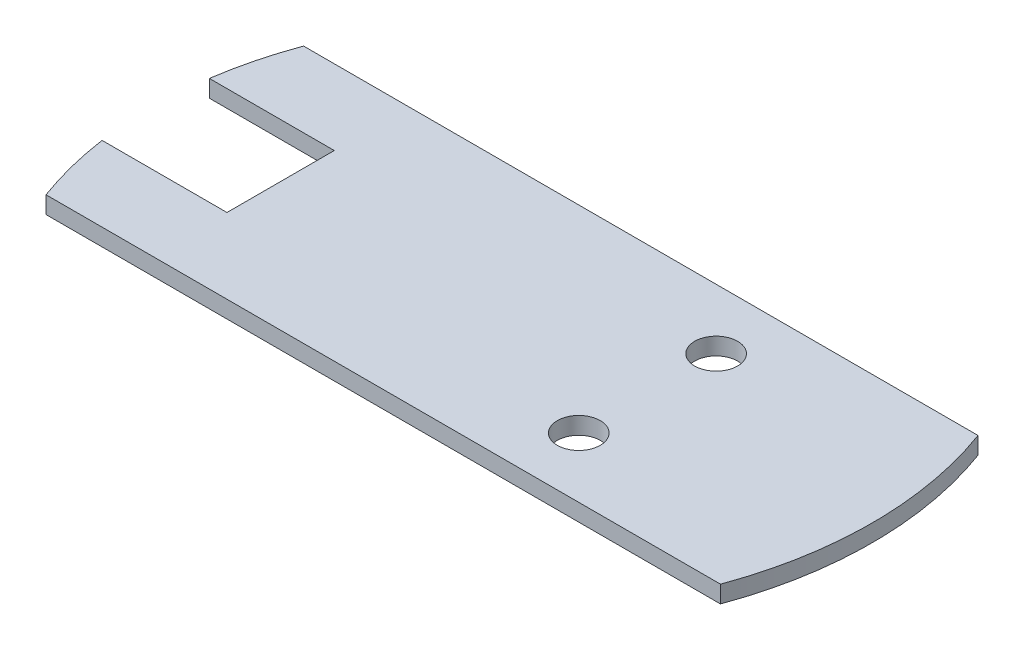
SolidWorks part; units mm, degrees
ref_plane "Front Plane" through (0, 0, 0) normal (0, 0, 1) x (1, 0, 0)
ref_plane "Top Plane" through (0, 0, 0) normal (0, 1, 0) x (1, 0, 0)
ref_plane "Right Plane" through (0, 0, 0) normal (1, 0, 0) x (0, 0, -1)
sketch "Sketch1" plane through (0, 0, 0) normal (0, 1, 0) x (1, 0, 0)
  line L0 (-145.5499, 0) -> (145.5499, 0) construction
  line L1 (-39.2787, 15) -> (39.2787, 15)
  line L2 (-39.2787, 15) -> (-39.2787, -15) construction
  line L3 (-39.2787, -15) -> (39.2787, -15)
  line L4 (39.2787, 15) -> (39.2787, -15) construction
  line L5 (-39.2787, 15) -> (39.2787, -15) construction
  line L6 (-39.2787, -15) -> (39.2787, 15) construction
  line L7 (0, 15) -> (0, -15) construction
  line L8 (-41.95, 85.2716) -> (-41.95, -85.2716) construction
  line L9 (41.95, 91.1525) -> (41.95, -91.1525) construction
  arc A0 (-39.2787, -15) -> (-39.2787, 15) centre (1.5, 0) cw
  arc A1 (39.2787, -15) -> (39.2787, 15) centre (-1.5, 0) ccw
  point P0 (0, 0)
  point P9 (0, 0)
  point P14 (0, 0)
  point P18 (-41.95, 0)
  point P21 (41.95, 0)
  dimension "D1" = 43.45
  dimension "D2" = 83.9
  dimension "D3" = 30
extrude "Boss-Extrude1" add sketch "Sketch1" along normal mid plane 2
sketch "Sketch2" plane through (0, 1, 0) normal (0, 1, 0) x (1, 0, 0)
  line L0 (0, 0) -> (-41.95, 0) construction
  line L1 (-41.95, 6.25) -> (-41.95, -6.25) construction
  line L2 (-26.95, -6.25) -> (-56.95, -6.25)
  line L3 (-26.95, -6.25) -> (-26.95, 6.25)
  line L4 (-26.95, 6.25) -> (-56.95, 6.25)
  line L5 (-56.95, -6.25) -> (-56.95, 6.25)
  line L6 (-26.95, -6.25) -> (-56.95, 6.25) construction
  line L7 (-26.95, 6.25) -> (-56.95, -6.25) construction
  arc A0 (-39.2787, 15) -> (-39.2787, -15) centre (1.5, 0) ccw construction
  point P6 (-41.95, 0)
  point P16 (-41.95, 0)
  dimension "D1" = 15
  dimension "D2" = 12.5
extrude "Cut-Extrude1" cut sketch "Sketch2" against normal up to next
sketch "Sketch3" plane through (0, -1, 0) normal (0, -1, 0) x (1, 0, 0)
  circle A0 centre (15.7787, 8) radius 2.5
  circle A1 centre (15.7787, -8) radius 2.5
  dimension "D1" = 5
extrude "Cut-Extrude2" cut sketch "Sketch3" against normal up to next
equation "\"D1@Sketch1\"=86.9/2"
